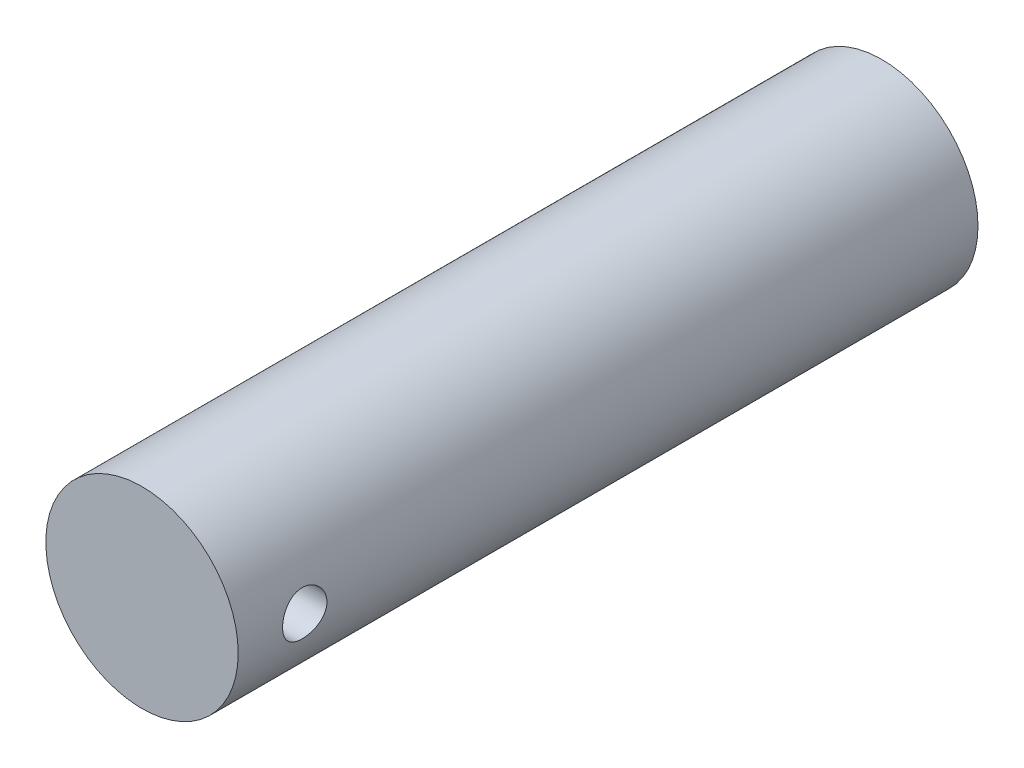
SolidWorks part; units mm, degrees
material "AISI 304"
ref_plane "Front" through (0, 0, 0) normal (0, 0, 1) x (1, 0, 0)
ref_plane "Top" through (0, 0, 0) normal (0, 1, 0) x (1, 0, 0)
ref_plane "Right" through (0, 0, 0) normal (1, 0, 0) x (0, 0, -1)
sketch "Sketch1" plane through (0, 0, 0) normal (0, 0, 1) x (1, 0, 0)
  circle A0 centre (0, 0) radius 6.5
  dimension "D1" = 13
extrude "Boss-Extrude1" add sketch "Sketch1" along normal blind 50
ref_plane "Plane1" through (6.5, 0, 0) normal (1, 0, 0) x (0, 0, -1)
sketch "Sketch2" plane through (6.5, 0, 0) normal (1, 0, 0) x (0, 0, -1)
  line L0 (-50, 6.5) -> (-50, -6.5) construction
  circle A0 centre (-45.5, 0) radius 1.5
  dimension "D2" = 3
  dimension "D1" = 4.5
extrude "Cut-Extrude1" cut sketch "Sketch2" against normal through all
